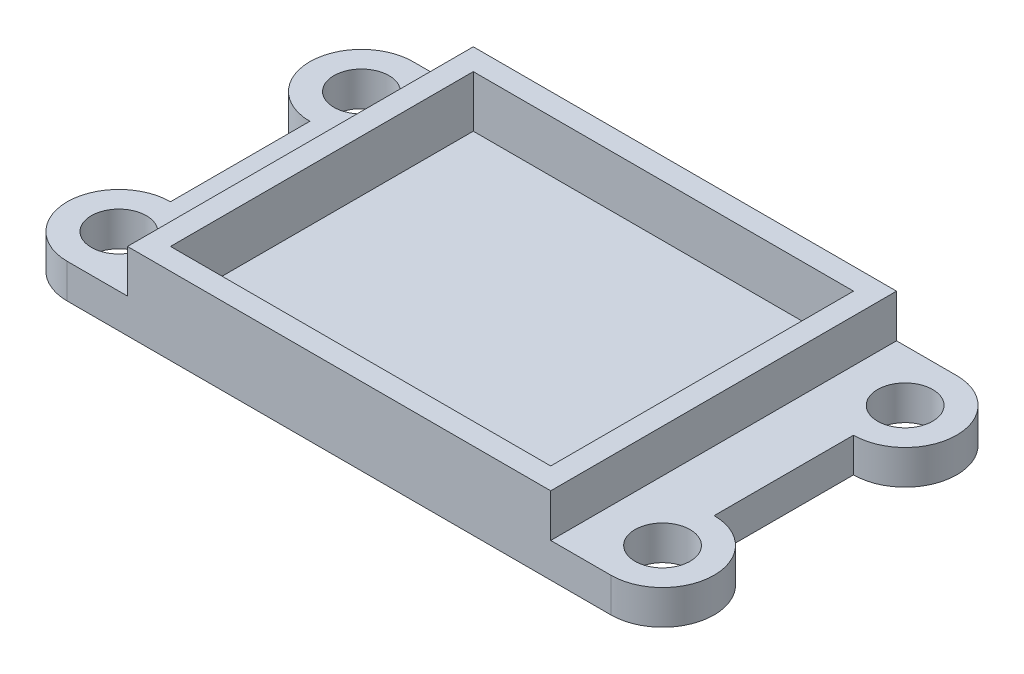
SolidWorks part; units mm, degrees
ref_plane "Front Plane" through (0, 0, 0) normal (0, 0, 1) x (1, 0, 0)
ref_plane "Top Plane" through (0, 0, 0) normal (0, 1, 0) x (1, 0, 0)
ref_plane "Right Plane" through (0, 0, 0) normal (1, 0, 0) x (0, 0, -1)
sketch "Sketch1" plane through (0, 0, 0) normal (0, 1, 0) x (1, 0, 0)
  line L0 (-12.3, 10.05) -> (-12.3, -10.05)
  line L1 (-10.8, 8.55) -> (10.8, 8.55) construction
  line L2 (-10.8, 8.55) -> (-10.8, -8.55) construction
  line L3 (-10.8, -8.55) -> (10.8, -8.55) construction
  line L4 (10.8, 8.55) -> (10.8, -8.55) construction
  line L5 (-12.3, -10.05) -> (12.3, -10.05)
  line L6 (12.3, 10.05) -> (12.3, -10.05)
  line L7 (-12.3, 10.05) -> (12.3, 10.05)
  point P4 (0, 8.55)
  point P6 (-10.8, 0)
  dimension "D1" = 21.6
  dimension "D2" = 17.1
  dimension "D6" = 1.5
extrude "Boss-Extrude1" add sketch "Sketch1" along normal blind 1.5
sketch "Sketch2" plane through (0, 1.5, 0) normal (0, 1, 0) x (1, 0, 0)
  line L0 (-11.05, 8.8) -> (-11.05, -8.8)
  line L1 (-12.3, 10.05) -> (12.3, 10.05)
  line L2 (-12.3, 10.05) -> (-12.3, -10.05)
  line L3 (-12.3, -10.05) -> (12.3, -10.05)
  line L4 (12.3, 10.05) -> (12.3, -10.05)
  line L5 (-11.05, -8.8) -> (11.05, -8.8)
  line L6 (11.05, 8.8) -> (11.05, -8.8)
  line L7 (-11.05, 8.8) -> (11.05, 8.8)
  dimension "D1" = 1.25
extrude "Boss-Extrude2" add sketch "Sketch2" along normal blind 3
sketch "Sketch3" plane through (0, 1.5, 0) normal (0, 1, 0) x (1, 0, 0)
  line L0 (11.05, -8.8) -> (11.05, 8.8) construction
  line L1 (-11.05, 8.8) -> (11.05, 8.8)
  line L2 (-11.05, 8.8) -> (-11.05, -3.8)
  line L3 (-11.05, -3.8) -> (11.05, -3.8)
  line L4 (11.05, 8.8) -> (11.05, -3.8)
  line L5 (-11.05, -8.8) -> (11.05, -8.8) construction
  circle A0 centre (-8.3, 6.05) radius 1.75
  dimension "D1" = 5
extrude "Boss-Extrude3" [suppressed] add sketch "Sketch3" along normal blind 1.5
sketch "Sketch4" plane through (0, 0, 0) normal (0, 1, 0) x (1, 0, 0)
  line L0 (12.3, -10.05) -> (12.3, 10.05) construction
  line L1 (15.8, 10.05) -> (12.3, 10.05)
  line L2 (15.8, 4.05) -> (12.3, 4.05)
  line L3 (12.3, -10.05) -> (12.3, 10.05) construction
  line L4 (12.3, 10.05) -> (12.3, 4.05)
  line L5 (0, 10.05) -> (0, -10.05) construction
  line L6 (12.3, 10.05) -> (-12.3, 10.05) construction
  line L7 (-12.3, -10.05) -> (12.3, -10.05) construction
  line L8 (-12.3, 0) -> (12.3, 0) construction
  line L9 (-12.3, 10.05) -> (-12.3, -10.05) construction
  line L10 (-15.8, 4.05) -> (-12.3, 4.05)
  line L11 (-12.3, 10.05) -> (-12.3, 4.05)
  line L12 (-15.8, 10.05) -> (-12.3, 10.05)
  line L13 (15.8, -4.05) -> (12.3, -4.05)
  line L14 (12.3, -10.05) -> (12.3, -4.05)
  line L15 (15.8, -10.05) -> (12.3, -10.05)
  line L16 (-15.8, -10.05) -> (-12.3, -10.05)
  line L17 (-12.3, -10.05) -> (-12.3, -4.05)
  line L18 (-15.8, -4.05) -> (-12.3, -4.05)
  circle A0 centre (15.8, 7.05) radius 1.6
  arc A1 (15.8, 4.05) -> (15.8, 10.05) centre (15.8, 7.05) ccw
  circle A2 centre (-15.8, 7.05) radius 1.6
  arc A3 (-15.8, 4.05) -> (-15.8, 10.05) centre (-15.8, 7.05) cw
  arc A4 (15.8, -4.05) -> (15.8, -10.05) centre (15.8, -7.05) cw
  circle A5 centre (15.8, -7.05) radius 1.6
  circle A6 centre (-15.8, -7.05) radius 1.6
  arc A7 (-15.8, -4.05) -> (-15.8, -10.05) centre (-15.8, -7.05) ccw
  dimension "D1" = 3.2
  dimension "D3" = 6
  dimension "D2" = 3.5
extrude "Boss-Extrude4" add sketch "Sketch4" along normal blind 2
sketch "Sketch5" [suppressed] plane through (0, 3, 0) normal (0, 1, 0) x (1, 0, 0)
  line L1 (-10.05, 7.8) -> (10.05, 7.8) construction
  line L2 (-10.05, 7.8) -> (-10.05, -2.8) construction
  line L3 (-10.05, -2.8) -> (10.05, -2.8) construction
  line L4 (10.05, 7.8) -> (10.05, -2.8) construction
  line L5 (-11.05, -3.8) -> (11.05, -3.8) construction
  line L6 (-9.05, 6.8) -> (-9.05, -1.8) construction
  line L7 (-9.05, -1.8) -> (9.05, -1.8) construction
  line L8 (9.05, 6.8) -> (9.05, -1.8) construction
  line L9 (-9.05, 6.8) -> (9.05, 6.8) construction
  line L10 (-9.05, -1.3) -> (-9.05, 2.05)
  line L11 (-8.55, 2.55) -> (-8.3, 2.55)
  line L12 (-4.8, 6.05) -> (-4.8, 6.3)
  line L13 (-4.3, 6.8) -> (8.55, 6.8)
  line L14 (9.05, 6.3) -> (9.05, -1.3)
  line L15 (8.55, -1.8) -> (-8.55, -1.8)
  circle A0 centre (-8.3, 6.05) radius 1.75 construction
  arc A1 (-8.3, 2.55) -> (-4.8, 6.05) centre (-8.3, 6.05) ccw
  arc A2 (-4.8, 6.3) -> (-4.3, 6.8) centre (-4.3, 6.3) cw
  arc A3 (8.55, 6.8) -> (9.05, 6.3) centre (8.55, 6.3) cw
  arc A4 (9.05, -1.3) -> (8.55, -1.8) centre (8.55, -1.3) cw
  arc A5 (-9.05, -1.3) -> (-8.55, -1.8) centre (-8.55, -1.3) ccw
  arc A6 (-9.05, 2.05) -> (-8.55, 2.55) centre (-8.55, 2.05) cw
  point P4 (0, -2.8)
  point P23 (-4.8, 6.8)
  dimension "D4" = 3.5
  dimension "D5" = 0.5
  dimension "D1" = 1
  dimension "D3" = 3.5
  dimension "D2" = 1
extrude "Cut-Extrude1" [suppressed] cut sketch "Sketch5" against normal through all
sketch "Sketch6" [suppressed] plane through (0, 1.5, 0) normal (0, 1, 0) x (1, 0, 0)
  line L1 (-11.05, -3.8) -> (11.05, -3.8)
  line L2 (-11.05, -3.8) -> (-11.05, -8.8)
  line L3 (-11.05, -8.8) -> (11.05, -8.8)
  line L4 (11.05, -3.8) -> (11.05, -8.8)
extrude "Cut-Extrude2" [suppressed] cut sketch "Sketch6" against normal through all
sketch "Sketch8" plane through (0, 2, 0) normal (0, 1, 0) x (1, 0, 0)
  line L1 (-15.8, 4.05) -> (-12.3, 4.05)
  line L2 (-15.8, 4.05) -> (-15.8, -4.05)
  line L3 (-15.8, -4.05) -> (-12.3, -4.05)
  line L4 (-12.3, 4.05) -> (-12.3, -4.05)
  line L5 (15.8, 4.05) -> (12.3, 4.05)
  line L6 (15.8, 4.05) -> (15.8, -4.05)
  line L7 (15.8, -4.05) -> (12.3, -4.05)
  line L8 (12.3, 4.05) -> (12.3, -4.05)
extrude "Boss-Extrude5" add sketch "Sketch8" against normal through all
